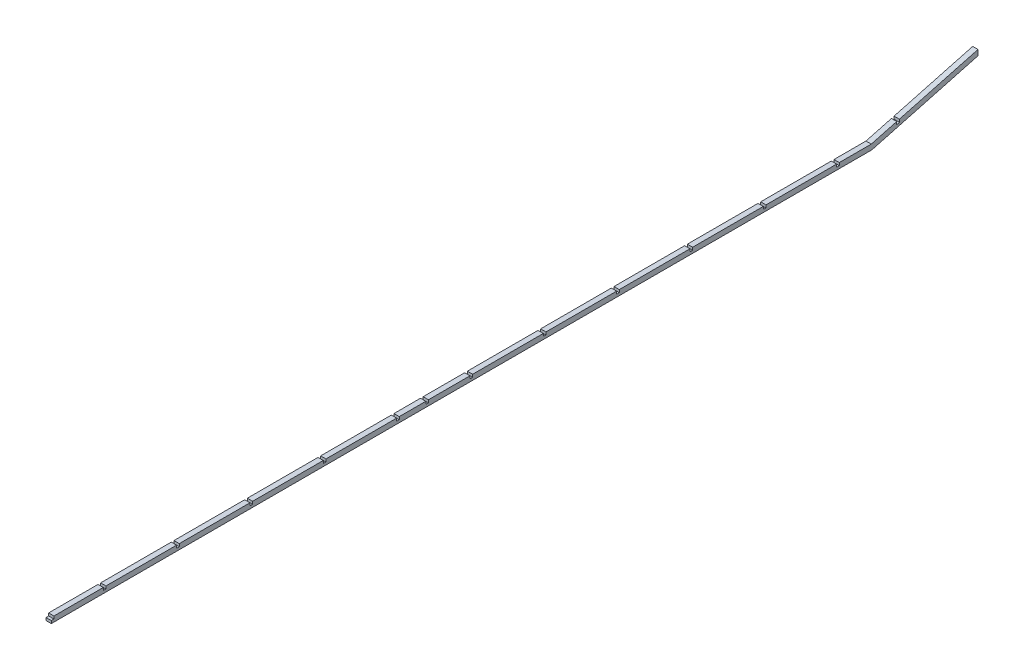
SolidWorks part; units mm, degrees
ref_plane "Спереди" through (0, 0, 0) normal (0, 0, 1) x (1, 0, 0)
ref_plane "Сверху" through (0, 0, 0) normal (0, 1, 0) x (1, 0, 0)
ref_plane "Справа" through (0, 0, 0) normal (1, 0, 0) x (0, 0, -1)
other "Configuration Table"
sketch "Эскиз1" plane through (0, 0, 0) normal (1, 0, 0) x (0, 0, -1)
  line L0 (-413.957, 0) -> (514.903, 0)
  line L1 (514.903, 0) -> (634.9, 32.1531)
  line L2 (-410.957, 6) -> (-355.097, 6)
  line L3 (-413.957, 0) -> (-413.957, 3)
  line L4 (-413.957, 3) -> (-410.957, 3)
  line L5 (-410.957, 3) -> (-410.957, 6)
  line L6 (514.903, 0) -> (513.9872, 6.9562) construction
  line L7 (634.9, 32.1531) -> (634.9, 38.3647)
  line L8 (514.1131, 6) -> (542.9052, 13.7148)
  line L9 (-355.097, 6) -> (-355.097, 3)
  line L10 (-355.097, 3) -> (-352.097, 3)
  line L11 (-352.097, 3) -> (-352.097, 6)
  line L12 (-272.097, 6) -> (-272.097, 3)
  line L13 (-272.097, 3) -> (-269.097, 3)
  line L14 (-269.097, 3) -> (-269.097, 6)
  line L15 (-189.097, 6) -> (-189.097, 3)
  line L16 (-189.097, 3) -> (-186.097, 3)
  line L17 (-186.097, 3) -> (-186.097, 6)
  line L18 (-106.097, 6) -> (-106.097, 3)
  line L19 (-106.097, 3) -> (-103.097, 3)
  line L20 (-103.097, 3) -> (-103.097, 6)
  line L21 (-23.097, 6) -> (-23.097, 3)
  line L22 (-23.097, 3) -> (-20.097, 3)
  line L23 (-20.097, 3) -> (-20.097, 6)
  line L24 (9.903, 6) -> (9.903, 3)
  line L25 (9.903, 3) -> (12.903, 3)
  line L26 (12.903, 3) -> (12.903, 6)
  line L27 (-352.097, 6) -> (-272.097, 6)
  line L28 (-269.097, 6) -> (-189.097, 6)
  line L29 (-186.097, 6) -> (-106.097, 6)
  line L30 (-103.097, 6) -> (-23.097, 6)
  line L31 (-20.097, 6) -> (9.903, 6)
  line L32 (12.903, 6) -> (59.903, 6)
  line L33 (59.903, 6) -> (59.903, 3)
  line L34 (59.903, 3) -> (62.903, 3)
  line L35 (62.903, 3) -> (62.903, 6)
  line L36 (142.903, 6) -> (142.903, 3)
  line L37 (142.903, 3) -> (145.903, 3)
  line L38 (145.903, 3) -> (145.903, 6)
  line L39 (225.903, 6) -> (225.903, 3)
  line L40 (225.903, 3) -> (228.903, 3)
  line L41 (228.903, 3) -> (228.903, 6)
  line L42 (308.903, 6) -> (308.903, 3)
  line L43 (308.903, 3) -> (311.903, 3)
  line L44 (311.903, 3) -> (311.903, 6)
  line L45 (391.903, 6) -> (391.903, 3)
  line L46 (391.903, 3) -> (394.903, 3)
  line L47 (394.903, 3) -> (394.903, 6)
  line L48 (474.903, 6) -> (474.903, 3)
  line L49 (474.903, 3) -> (477.903, 3)
  line L50 (477.903, 3) -> (477.903, 6)
  line L51 (477.903, 6) -> (514.1131, 6)
  line L52 (394.903, 6) -> (474.903, 6)
  line L53 (311.903, 6) -> (391.903, 6)
  line L54 (228.903, 6) -> (308.903, 6)
  line L55 (145.903, 6) -> (225.903, 6)
  line L56 (62.903, 6) -> (142.903, 6)
  line L57 (542.9052, 13.7148) -> (542.9052, 7.5032) construction
  line L58 (545.9052, 14.5187) -> (545.9052, 8.307) construction
  line L59 (542.9052, 10.609) -> (545.9052, 11.4128)
  line L60 (542.9052, 10.609) -> (542.9052, 13.7148)
  line L61 (545.9052, 11.4128) -> (545.9052, 14.5187)
  line L62 (545.9052, 14.5187) -> (634.9, 38.3647)
  dimension "D1" = 928.86
  dimension "D2" = 15
  dimension "D3" = 124.23
  dimension "D4" = 3
  dimension "D5" = 3
  dimension "D6" = 3
  dimension "D7" = 82.5
  dimension "D8" = 7.0163
  dimension "D9" = 3
  dimension "D10" = 55.86
  dimension "D11" = 3
  dimension "D12" = 3
  dimension "D13" = 3
  dimension "D14" = 3
  dimension "D15" = 3
  dimension "D16" = 80
  dimension "D17" = 80
  dimension "D18" = 30
  dimension "D19" = 80
  dimension "D20" = 80
  dimension "D21" = 3
  dimension "D22" = 3
  dimension "D23" = 3
  dimension "D24" = 3
  dimension "D25" = 3
  dimension "D26" = 47
  dimension "D27" = 80
  dimension "D28" = 80
  dimension "D29" = 80
  dimension "D30" = 80
  dimension "D31" = 3
  dimension "D32" = 80
  dimension "D33" = 28.99
  dimension "D34" = 3
extrude "Бобышка-Вытянуть1" add sketch "Эскиз1" along normal blind 6
